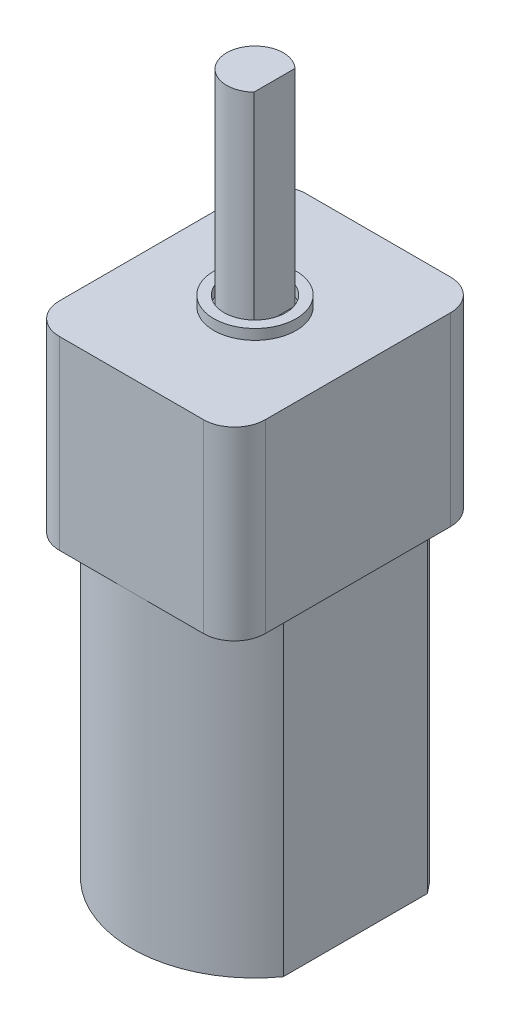
SolidWorks part; units mm, degrees
ref_plane "前视基准面" through (0, 0, 0) normal (0, 0, 1) x (1, 0, 0)
ref_plane "上视基准面" through (0, 0, 0) normal (0, 1, 0) x (1, 0, 0)
ref_plane "右视基准面" through (0, 0, 0) normal (1, 0, 0) x (0, 0, -1)
sketch "草图1" plane through (0, 0, 0) normal (0, 1, 0) x (1, 0, 0)
  line L0 (4.8734, -3.5) -> (4.8734, 3.5)
  line L1 (0, 10.5975) -> (0, -10.9986) construction
  line L2 (-4.8734, -3.5) -> (-4.8734, 3.5)
  arc A0 (4.8734, 3.5) -> (-4.8734, 3.5) centre (0, 0) ccw
  arc A1 (-4.8734, -3.5) -> (4.8734, -3.5) centre (0, 0) ccw
  dimension "D1" = 12
  dimension "D2" = 7
extrude "凸台-拉伸1" add sketch "草图1" along normal blind 15
sketch "草图2" plane through (0, 15, 0) normal (0, 1, 0) x (1, 0, 0)
  line L1 (-5, 6) -> (5, 6)
  line L2 (-5, 6) -> (-5, -6)
  line L3 (-5, -6) -> (5, -6)
  line L4 (5, 6) -> (5, -6)
  dimension "D1" = 10
  dimension "D2" = 5
  dimension "D3" = 12
  dimension "D4" = 6
extrude "凸台-拉伸2" add sketch "草图2" along normal blind 9
fillet "圆角1" radius 1.5 4 edges at (-5, 19.5, 6) (-5, 19.5, -6) (5, 19.5, 6) (5, 19.5, -6)
sketch "草图3" plane through (0, 24, 0) normal (0, 1, 0) x (1, 0, 0)
  circle A0 centre (0, 0) radius 2
  circle A1 centre (0, 0) radius 1.5
extrude "凸台-拉伸3" add sketch "草图3" along normal blind 0.5
sketch "草图4" plane through (0, 24, 0) normal (0, 1, 0) x (1, 0, 0)
  line L0 (0.9437, 1) -> (0.9437, -1)
  arc A0 (0.9437, 1) -> (0.9437, -1) centre (0, 0) ccw
  dimension "D1" = 2.75
  dimension "D2" = 2
extrude "凸台-拉伸4" add sketch "草图4" along normal blind 10
sketch "草图5" plane through (0, 0, 0) normal (0, -1, 0) x (1, 0, 0)
  circle A0 centre (0, 0) radius 2.5
extrude "凸台-拉伸5" add sketch "草图5" along normal blind 1.5
sketch "草图6" plane through (0, -1.5, 0) normal (0, -1, 0) x (1, 0, 0)
  circle A0 centre (0, 0) radius 0.75
extrude "切除-拉伸1" cut sketch "草图6" against normal blind 0.5
